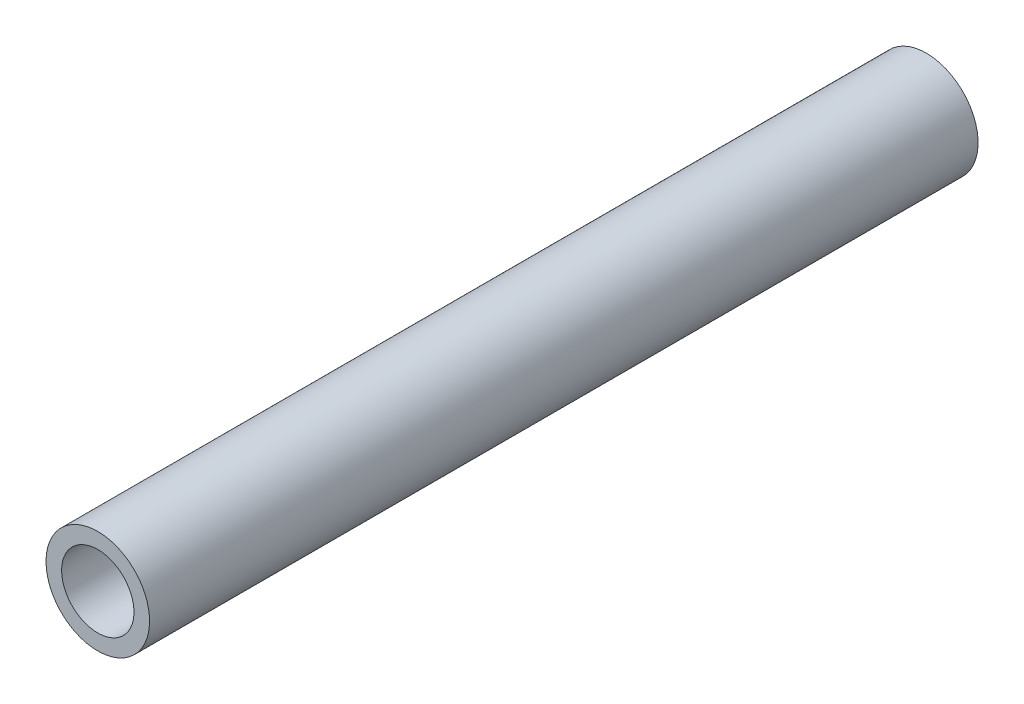
SolidWorks part; units mm, degrees
ref_plane "Front Plane" through (0, 0, 0) normal (0, 0, 1) x (1, 0, 0)
ref_plane "Top Plane" through (0, 0, 0) normal (0, 1, 0) x (1, 0, 0)
ref_plane "Right Plane" through (0, 0, 0) normal (1, 0, 0) x (0, 0, -1)
sketch "Sketch1" plane through (0, 0, 0) normal (0, 0, 1) x (1, 0, 0)
  circle A0 centre (0, 0) radius 9.525
  dimension "D1" = 19.05
extrude "Extrude-Thin1" add sketch "Sketch1" along normal blind 152.4 thin thin type one direction reverse wall 2.8702
